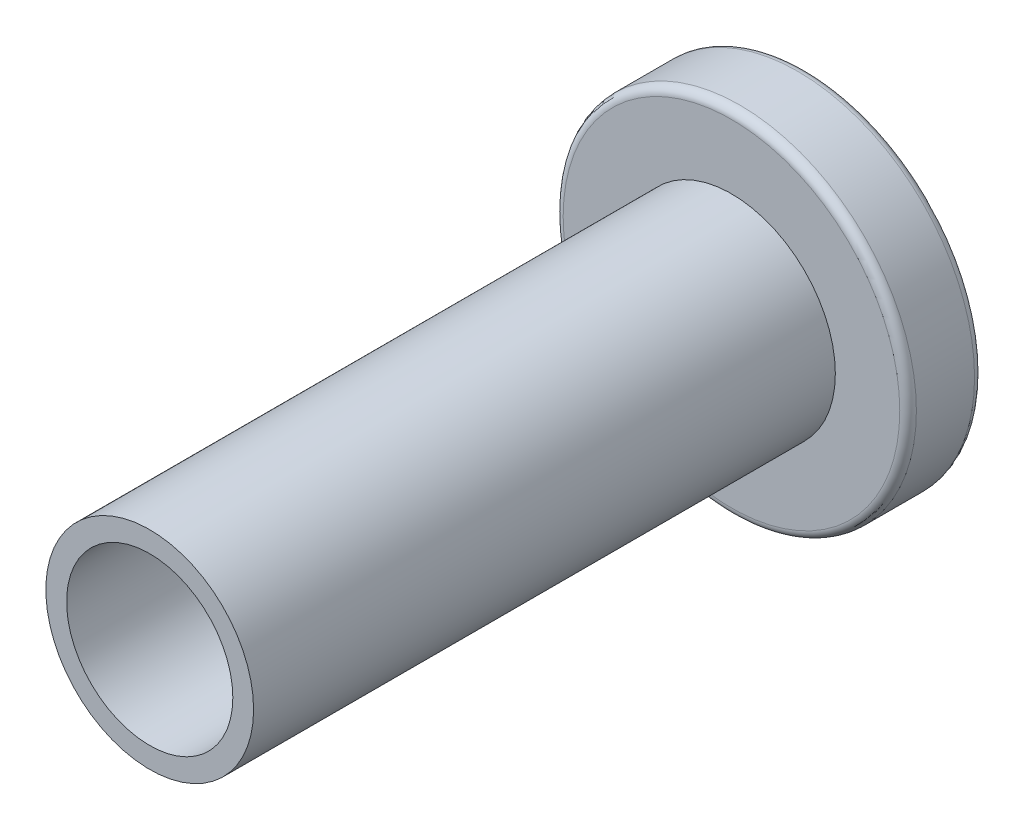
SolidWorks part; units mm, degrees
material "AISI 304"
ref_plane "前视基准面" through (0, 0, 0) normal (0, 0, 1) x (1, 0, 0)
ref_plane "上视基准面" through (0, 0, 0) normal (0, 1, 0) x (1, 0, 0)
ref_plane "右视基准面" through (0, 0, 0) normal (1, 0, 0) x (0, 0, -1)
other "Configuration Table"
sketch "草图1" plane through (0, 0, 0) normal (0, 0, 1) x (1, 0, 0)
  circle A0 centre (0, 0) radius 4.25
  dimension "D1" = 8.5
extrude "凸台-拉伸1" add sketch "草图1" along normal blind 1.8
sketch "草图2" plane through (0, 0, 1.8) normal (0, 0, 1) x (1, 0, 0)
  circle A0 centre (0, 0) radius 2.5
  circle A1 centre (0, 0) radius 2
  dimension "D1" = 5
  dimension "D2" = 4
extrude "凸台-拉伸2" add sketch "草图2" along normal blind 14
fillet "圆角1" radius 0.2 2 edges at (4.25, 0, 0) (4.25, 0, 1.8)
sketch "草图3" plane through (0, 0, 0) normal (0, 0, -1) x (-1, 0, 0)
  line L0 (0, 0) -> (1.4434, 0) construction
  line L1 (1.4434, 0) -> (0.7217, 1.25)
  line L2 (0.7217, 1.25) -> (-0.7217, 1.25)
  line L3 (-0.7217, 1.25) -> (-1.4434, 0)
  line L4 (-1.4434, 0) -> (-0.7217, -1.25)
  line L5 (-0.7217, -1.25) -> (0.7217, -1.25)
  line L6 (0.7217, -1.25) -> (1.4434, 0)
  circle A0 centre (0, 0) radius 1.25 construction
  dimension "D1" = 2.5
extrude "切除-拉伸1" cut sketch "草图3" against normal blind 1.5
